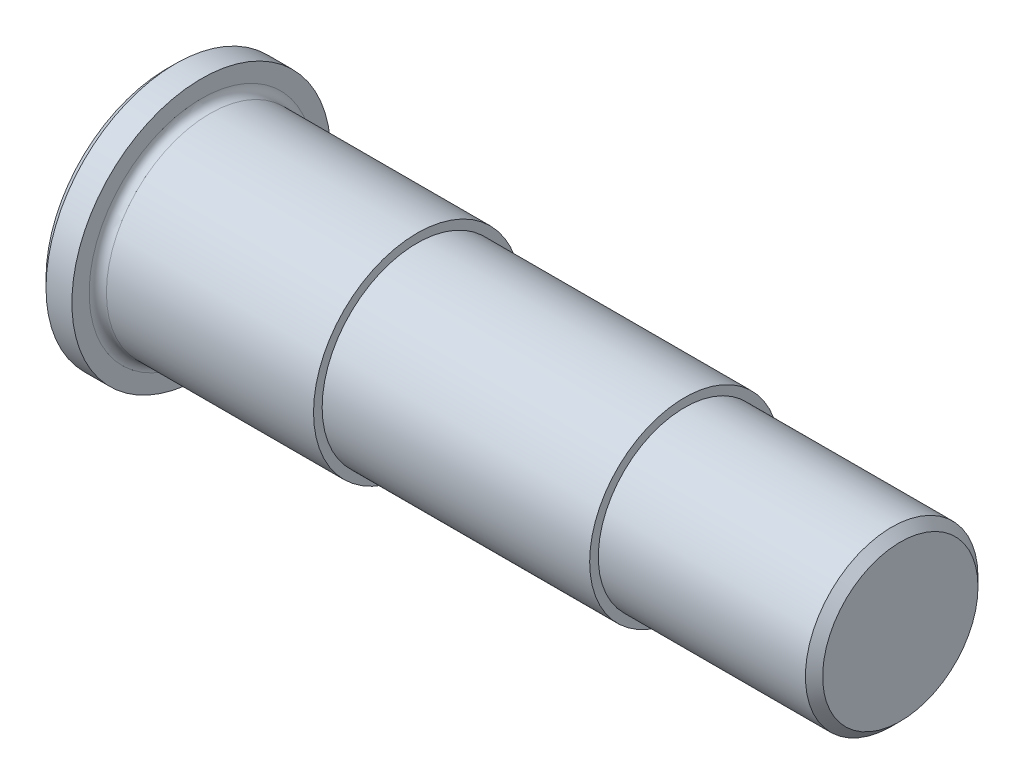
SolidWorks part; units mm, degrees
material "1.4401 (X5CrNiMo17-12-2)"
ref_plane "Спереди" through (0, 0, 0) normal (0, 0, 1) x (1, 0, 0)
ref_plane "Сверху" through (0, 0, 0) normal (0, 1, 0) x (1, 0, 0)
ref_plane "Справа" through (0, 0, 0) normal (1, 0, 0) x (0, 0, -1)
sketch "Эскиз1" plane through (0, 0, 0) normal (0, 0, 1) x (1, 0, 0)
  line L0 (0, 15) -> (0, 0)
  line L1 (0, 0) -> (4, 0)
  line L2 (4, 0) -> (4, 15)
  line L3 (4, 15) -> (0, 15)
  line L4 (0, 0) -> (4, 0) construction
revolve "Повернуть1" add sketch "Эскиз1" angle 360 about L4
sketch "Эскиз2" plane through (4, 0, 0) normal (1, 0, 0) x (0, 0, -1)
  circle A0 centre (0, 0) radius 12
extrude "Бобышка-Вытянуть1" add sketch "Эскиз2" along normal blind 25
sketch "Эскиз3" plane through (29, 0, 0) normal (1, 0, 0) x (0, 0, -1)
  circle A0 centre (0, 0) radius 11
extrude "Бобышка-Вытянуть2" add sketch "Эскиз3" along normal blind 31
sketch "Эскиз4" plane through (60, 0, 0) normal (1, 0, 0) x (0, 0, -1)
  circle A0 centre (0, 0) radius 10
extrude "Бобышка-Вытянуть3" add sketch "Эскиз4" along normal blind 25
ref_plane "Плоскость4" through (80, 0, 0) normal (-1, 0, 0) x (0, -1, 0)
sketch "Эскиз5" plane through (80, 0, 0) normal (-1, 0, 0) x (0, -1, 0)
  line L0 (7.1414, -7) -> (-7.1414, -7)
  arc A0 (-7.1414, -7) -> (7.1414, -7) centre (0, 0) ccw
extrude "Вырез-Вытянуть1" cut sketch "Эскиз5" against normal blind 3
chamfer "Фаска1" distance 1 angle 45 2 edges at (0, 0, -15) (85, 0, -10)
fillet "Скругление1" radius 1 1 edges at (4, 0, -12)
